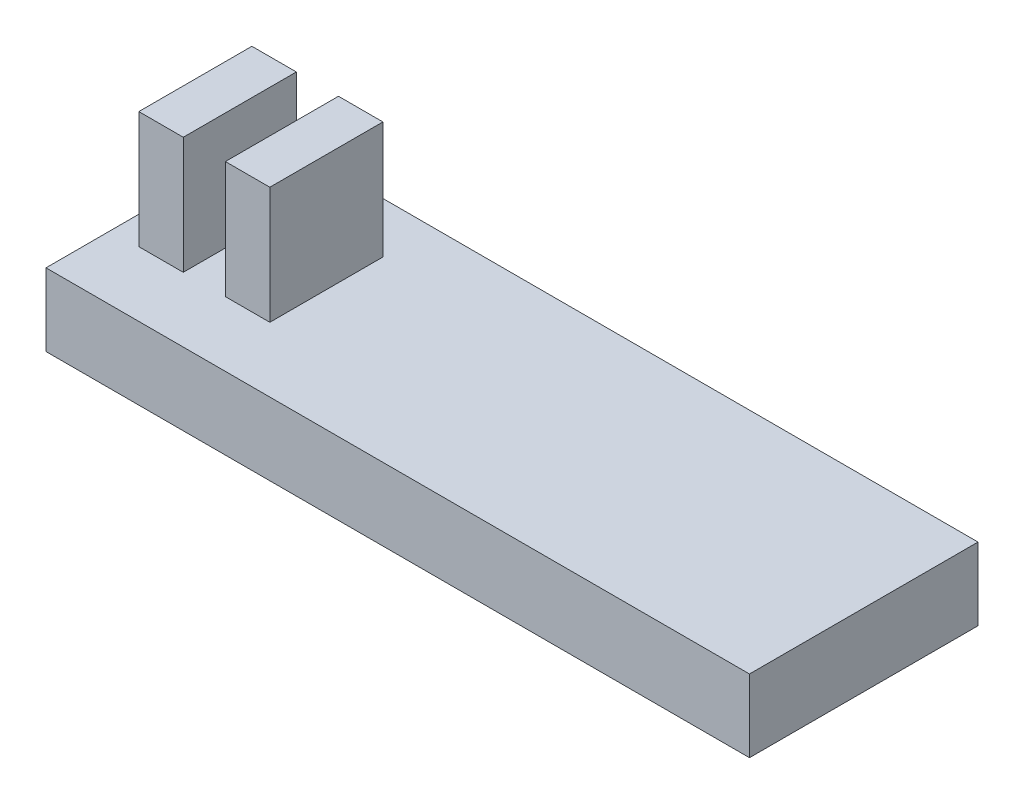
SolidWorks part; units mm, degrees
ref_plane "Front Plane" through (0, 0, 0) normal (0, 0, 1) x (1, 0, 0)
ref_plane "Top Plane" through (0, 0, 0) normal (0, 1, 0) x (1, 0, 0)
ref_plane "Right Plane" through (0, 0, 0) normal (1, 0, 0) x (0, 0, -1)
sketch "Sketch1" plane through (0, 0, 0) normal (0, 1, 0) x (1, 0, 0)
  line L1 (-45.1, 14.65) -> (45.1, 14.65)
  line L2 (-45.1, 14.65) -> (-45.1, -14.65)
  line L3 (-45.1, -14.65) -> (45.1, -14.65)
  line L4 (45.1, 14.65) -> (45.1, -14.65)
  line L5 (-45.1, 14.65) -> (45.1, -14.65) construction
  line L6 (-45.1, -14.65) -> (45.1, 14.65) construction
  point P0 (0, 0)
  dimension "D1" = 29.3
  dimension "D2" = 90.2
extrude "Boss-Extrude1" add sketch "Sketch1" along normal blind 9.3
sketch "Sketch2" plane through (0, 9.3, 0) normal (0, 1, 0) x (1, 0, 0)
  line L0 (-45.1, 14.65) -> (-45.1, -14.65) construction
  line L1 (-41.5, 8.15) -> (-35.8, 8.15)
  line L2 (-41.5, 8.15) -> (-41.5, -6.35)
  line L3 (-41.5, -6.35) -> (-35.8, -6.35)
  line L4 (-35.8, 8.15) -> (-35.8, -6.35)
  line L5 (-30.4, 8.15) -> (-24.7, 8.15)
  line L6 (-30.4, 8.15) -> (-30.4, -6.35)
  line L7 (-30.4, -6.35) -> (-24.7, -6.35)
  line L8 (-24.7, 8.15) -> (-24.7, -6.35)
  line L9 (45.1, 14.65) -> (-45.1, 14.65) construction
  dimension "D1" = 14.5
  dimension "D2" = 5.7
  dimension "D3" = 5.4
  dimension "D4" = 3.6
  dimension "D5" = 6.5
extrude "Boss-Extrude2" add sketch "Sketch2" along normal blind 15
